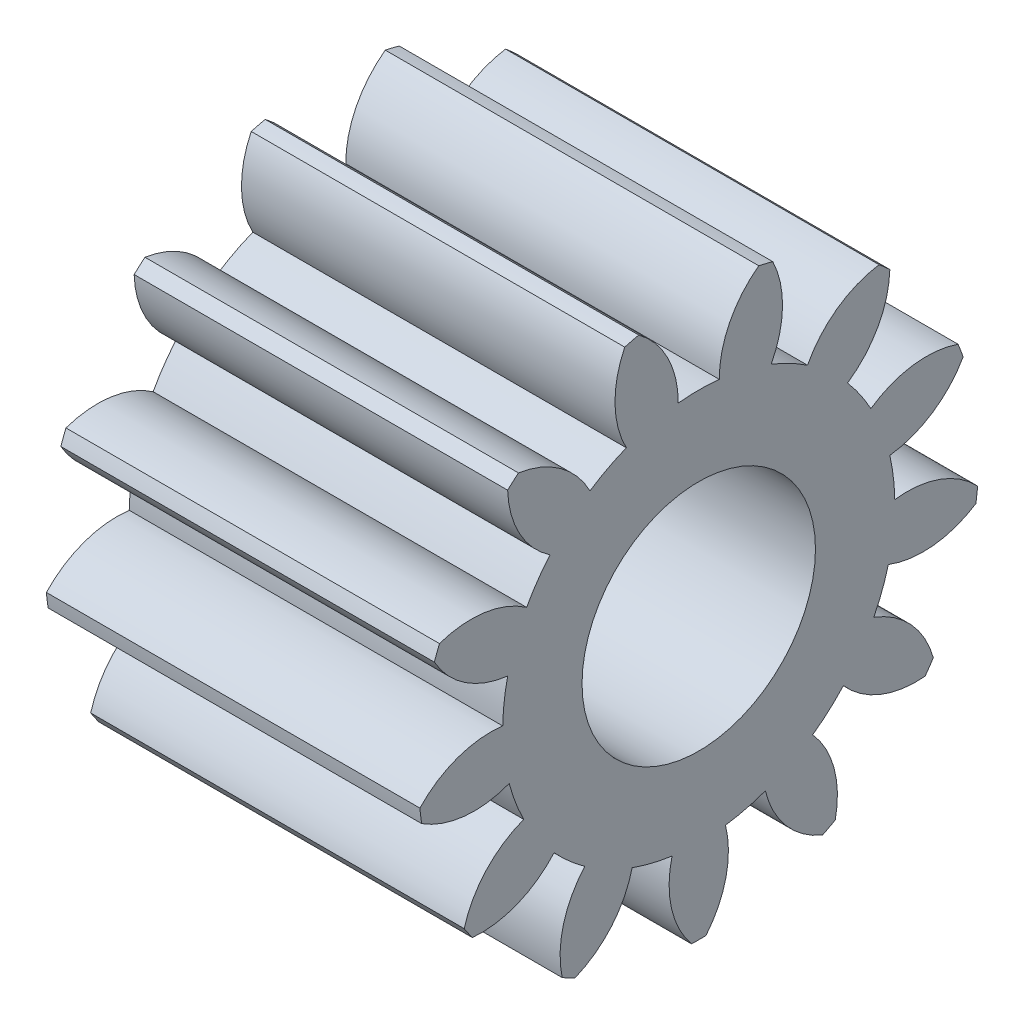
SolidWorks part; units mm, degrees
ref_plane "Plane1" through (0, 0, 0) normal (0, 0, 1) x (1, 0, 0)
ref_plane "Plane2" through (0, 0, 0) normal (0, 1, 0) x (1, 0, 0)
ref_plane "Plane3" through (0, 0, 0) normal (1, 0, 0) x (0, 0, -1)
other "Configuration Table"
sketch "HoldingSke" plane through (0, 0, 0) normal (0, 1, 0) x (1, 0, 0)
  line L0 (0, 0) -> (1.218, -0.2812)
  line L1 (-15, 0) -> (100, 0) construction
  line L2 (0, 0) -> (-2.1039, 2.3779)
  line L3 (0, 0) -> (-11.863, 4.5341)
  line L4 (0, 0) -> (8.4147, 1.9427)
  line L5 (0, 0) -> (-46.8476, -17.4728)
  line L6 (0, 0) -> (-6.6317, -4.4744)
  line L7 (-2.1039, 2.3779) -> (8.6586, 51.2059)
  line L8 (-76.2, 54.61) -> (-75.3, 54.61)
  line L9 (-71.009, 38.7566) -> (-53.1078, 45.2721)
  line L10 (-76.2, 71.12) -> (104.1128, 71.12)
  line L11 (0, 0) -> (-8, 0)
  line L12 (-76.2, 101.6) -> (-76.17, 101.6)
  line L13 (24.9733, 27.94) -> (52.9518, 28.4284)
  line L14 (24.9733, 27.94) -> (24.9743, 27.94)
  line L15 (24.9733, 27.94) -> (100.4006, 29.5858)
  line L16 (-63.627, -0.8) -> (-12.827, -0.8)
  circle A0 centre (0, 0) radius 2.5
  circle A1 centre (0, 0) radius 4.199
  circle A2 centre (0, 0) radius 37.5
  circle A3 centre (0, 0) radius 2.5
  dimension "MHD" = 8.398
  dimension "Hub_dia" = 75
  dimension "Bore" = 5
  dimension "MBD" = 5
  dimension "Num_teeth" = 13
  dimension "Pitch" = 1.25
  dimension "Overall_len" = 50
  dimension "Show_teeth" = 13
  dimension "Thickness" = 8
  dimension "OAL" = 50.0001
  dimension "T_dim" = 0.9
  dimension "Ap" = 20
  dimension "H" = 19.05
  dimension "Pitch_radius" = 180.3128
  dimension "Width" = 8
  dimension "Backlash" = 0.03
  dimension "Addendum_fac" = 1
  dimension "Dedendum_fac" = 1.25
  dimension "Clearance_fac" = 0.25
  dimension "Dedendum_add" = 0.001
  dimension "Module" = 0.8
sketch "BasProSke" plane through (0, 0, 0) normal (0, 1, 0) x (1, 0, 0)
  line L0 (-10, 0) -> (60, 0) construction
  line L1 (0, 0) -> (0, 6)
  line L2 (0, 0) -> (8, 0)
  line L3 (8, 0) -> (8, 6)
  line L4 (8, 6) -> (0, 6)
  dimension "Thickness" = 8
  dimension "Diameter" = 12
revolve "Base-Revolve" add sketch "BasProSke" angle 360 about L0
sketch "TooCutSke" plane through (0, 0, 0) normal (1, 0, 0) x (0, 0, -1)
  line L1 (0, 0) -> (0, 107) construction
  line L2 (0, 0) -> (-0.6792, 5.1554) construction
  line L3 (0, 0) -> (-2.4737, 10.036) construction
  line L4 (-0.6792, 5.1554) -> (-1.2368, 5.018) construction
  arc A0 (0.4398, 4.1759) -> (-0.4398, 4.1759) centre (0, 0) ccw
  arc A1 (1.3129, 5.8806) -> (-1.3129, 5.8806) centre (0, 0) ccw
  circle A2 centre (0, 0) radius 5.2 construction
  circle A3 centre (0, 0) radius 4.8864 construction
  arc A4 (-0.4398, 4.1759) -> (-1.3129, 5.8806) centre (-2.5198, 4.1866) ccw
  arc A5 (1.3129, 5.8806) -> (0.4398, 4.1759) centre (2.5198, 4.1866) ccw
  dimension "Root_dia" = 8.398
  dimension "Overcut_dia" = 12.0508
  dimension "Pitch_dia" = 10.4
  dimension "Base_dia" = 9.7728
  dimension "Flank_rad" = 2.08
  dimension "Half_ang" = 13.846
  dimension "Half_CT" = 0.5743
extrude "ToothCut" cut sketch "TooCutSke" along normal through all
fillet "Breaks" [suppressed] radius 0.016
fillet "RootFillets" [suppressed] radius 0.201
pattern_circular "TeethCuts" count 13 every 27.692 about axis through (-10, 0, 0) along (1, 0, 0) of "ToothCut", "RootFillets", "Breaks"
sketch "HubNeaOneSke" plane through (0, 0, 0) normal (-1, 0, 0) x (0, 0, 1)
  circle A0 centre (0, 0) radius 4.199
  dimension "Diameter" = 8.398
extrude "HubNearOne" [suppressed] add sketch "HubNeaOneSke" along normal blind 42.0001
sketch "HubNeaBotSke" plane through (0, 0, 0) normal (-1, 0, 0) x (0, 0, 1)
  circle A0 centre (0, 0) radius 4.199
  dimension "Diameter" = 8.398
extrude "HubNearBoth" [suppressed] add sketch "HubNeaBotSke" along normal blind 21
ref_plane "FarPln" through (8, 0, 0) normal (1, 0, 0) x (0, 0, -1)
sketch "HubFarSke" plane through (8, 0, 0) normal (1, 0, 0) x (0, 0, -1)
  circle A0 centre (0, 0) radius 4.199
  dimension "Diameter" = 8.398
extrude "HubFar" [suppressed] add sketch "HubFarSke" along normal blind 21
sketch "BorSke" plane through (0, 0, 0) normal (1, 0, 0) x (0, 0, -1)
  circle A0 centre (0, 0) radius 2.5
  dimension "Diameter" = 5
extrude "Bore" cut sketch "BorSke" along normal mid plane 100.0001
sketch "KeySke" plane through (0, 0, 0) normal (1, 0, 0) x (0, 0, -1)
  line L0 (-1, 0) -> (-1, 3.4)
  line L1 (-1, 3.4) -> (1, 3.4)
  line L2 (1, 3.4) -> (1, 0)
  line L3 (0, 0) -> (0, 34) construction
  line L4 (-1, 0) -> (1, 0)
  dimension "Offset" = 3.4
  dimension "Width" = 2
extrude "Keyway" [suppressed] cut sketch "KeySke" along normal mid plane 100.0001
pattern_circular "Keyway2" [suppressed] count 2 every 90 about axis through (-10, 0, 0) along (1, 0, 0)
equation "' \"Module@HoldingSke\" = 6.35"
equation "' \"Num_teeth@HoldingSke\" = 12"
equation "' \"Ap@HoldingSke\" =  20"
equation "' \"Ap@HoldingSke\" = 20"
equation "' \"Width@HoldingSke\" = 0.5 * 25.4"
equation "' \"Hub_dia@HoldingSke\"= 1 * 25.4"
equation "' \"Hub_dia@HoldingSke\" = 1 * 25.4"
equation "' \"Overall_len@HoldingSke\" = 1.0 * 25.4"
equation "' \"Bore@HoldingSke\" = 0.75 * 25.4"
equation "' \"T_dim@HoldingSke\" = 0.1 * 25.4"
equation "' \"Width@KeySke\" = 0.25 * 25.4"
equation "' \"Show_teeth@HoldingSke\" = 13"
equation "' \"Backlash@HoldingSke\" = 0.009 * 25.4"
equation "' \"Addendum_fac@HoldingSke\" = 1.0"
equation "' \"Dedendum_fac@HoldingSke\" = 1.25"
equation "' \"Dedendum_add@HoldingSke\" = 0.00005 * 25.4"
equation "' \"Clearance_fac@HoldingSke\" = 0.25"
equation "\"Pitch@HoldingSke\" = 1 / \"Module@HoldingSke\""
equation "\"Overcut_dia@TooCutSke\" = (\"Num_teeth@HoldingSke\" + 2 * \"Addendum_fac@HoldingSke\") / \"Pitch@HoldingSke\" + 0.002 * 25.4"
equation "\"Pitch_dia@TooCutSke\" = \"Num_teeth@HoldingSke\" / \"Pitch@HoldingSke\""
equation "\"Base_dia@TooCutSke\" = \"Num_teeth@HoldingSke\" / \"Pitch@HoldingSke\" * cos((\"Ap@HoldingSke\"  * 3.14159265 / 180))"
equation "\"Root_dia@TooCutSke\" = (\"Num_teeth@HoldingSke\" + 2) / \"Pitch@HoldingSke\" - 2 * (\"Addendum_fac@HoldingSke\" + \"Dedendum_fac@HoldingSke\") / \"Pitch@HoldingSke\" - \"Dedendum_add@HoldingSke\" * 2"
equation "\"Half_ang@TooCutSke\" = 180 / \"Num_teeth@HoldingSke\""
equation "\"Half_CT@TooCutSke\" = \"Num_teeth@HoldingSke\" / \"Pitch@HoldingSke\" * sin((3.14159265 / 2 / \"Num_teeth@HoldingSke\")) / 2 - 7 * \"Backlash@HoldingSke\" / 4"
equation "\"Flank_rad@TooCutSke\" = \"Num_teeth@HoldingSke\" / \"Pitch@HoldingSke\" / 5"
equation "\"Radius@RootFillets\" = \"Clearance_fac@HoldingSke\" / \"Pitch@HoldingSke\" + \"Dedendum_add@HoldingSke\""
equation "\"Break_rad@Breaks\" = 0.02 / \"Pitch@HoldingSke\""
equation "\"Thickness@HoldingSke\" = \"Width@HoldingSke\""
equation "\"OAL@HoldingSke\" = \"Thickness@HoldingSke\""
equation "\"MHD@HoldingSke\" = (\"Num_teeth@HoldingSke\" + 2) / \"Pitch@HoldingSke\" - 2 * (\"Addendum_fac@HoldingSke\" + \"Dedendum_fac@HoldingSke\")  / \"Pitch@HoldingSke\" - \"Dedendum_add@HoldingSke\" * 2"
equation "\"MBD@HoldingSke\" = (\"Num_teeth@HoldingSke\" + 2) / \"Pitch@HoldingSke\" - 2 * (\"Addendum_fac@HoldingSke\" + \"Dedendum_fac@HoldingSke\")  / \"Pitch@HoldingSke\" - \"Dedendum_add@HoldingSke\" * 2 - 0.002 * 25.4"
equation "\"MHD@HoldingSke\" = ((sgn( \"MHD@HoldingSke\" - \"Hub_dia@HoldingSke\" )-1)*( \"MHD@HoldingSke\" - \"Hub_dia@HoldingSke\" ))/-2+ \"Hub_dia@HoldingSke\""
equation "\"MBD@HoldingSke\" = ((sgn( \"MBD@HoldingSke\" - \"Bore@HoldingSke\" )-1)*( \"MBD@HoldingSke\" - \"Bore@HoldingSke\" ))/-2+ \"Bore@HoldingSke\""
equation "\"OAL@HoldingSke\" = ((sgn( \"OAL@HoldingSke\" - \"Overall_len@HoldingSke\" )+1)*( \"OAL@HoldingSke\" - \"Overall_len@HoldingSke\" ))/2 + \"Overall_len@HoldingSke\" + 0.000002 * 25.4"
equation "\"Num_teeth@TeethCuts\" = int( \"Show_teeth@HoldingSke\" ) + 1"
equation "\"Num_teeth@TeethCuts\" = ((sgn( \"Num_teeth@TeethCuts\" - \"Num_teeth@HoldingSke\" )-1)*( \"Num_teeth@TeethCuts\" - \"Num_teeth@HoldingSke\" ))/-2+ \"Num_teeth@HoldingSke\""
equation "\"Num_teeth@TeethCuts\" = ((sgn( \"Num_teeth@TeethCuts\" - 2.0)+1)*( \"Num_teeth@TeethCuts\" - 2.0))/2 +2.0"
equation "\"Angle@TeethCuts\" = 360.0 / \"Num_teeth@HoldingSke\""
equation "\"Diameter@BasProSke\" = (\"Num_teeth@HoldingSke\" + 2 * \"Addendum_fac@HoldingSke\") / \"Pitch@HoldingSke\""
equation "\"Thickness@BasProSke\"  = \"Thickness@HoldingSke\""
equation "' \"Fillet_rad@BasProSke\" =  \"Thickness@HoldingSke\" * 0.05"
equation "' \"Fillet_rad@BasProSke\" = \"Thickness@HoldingSke\" * 0.05"
equation "\"MHD@HoldingSke\" = ((sgn( \"MHD@HoldingSke\" - \"Root_dia@TooCutSke\" )-1)*( \"MHD@HoldingSke\" - \"Root_dia@TooCutSke\" ))/-2+ \"Root_dia@TooCutSke\""
equation "\"Diameter@HubNeaOneSke\" = \"MHD@HoldingSke\""
equation "\"Length@HubNearOne\" = \"OAL@HoldingSke\" - \"Thickness@BasProSke\""
equation "\"Diameter@HubNeaBotSke\" = \"MHD@HoldingSke\""
equation "\"Length@HubNearBoth\" = ( \"OAL@HoldingSke\" - \"Thickness@BasProSke\" ) / 2.0"
equation "\"Thickness@FarPln\" = \"Thickness@BasProSke\""
equation "\"Diameter@HubFarSke\" = \"MHD@HoldingSke\""
equation "\"Length@HubFar\" = ( \"OAL@HoldingSke\" - \"Thickness@BasProSke\" ) / 2.0"
equation "\"Diameter@BorSke\" = \"MBD@HoldingSke\""
equation "\"D1@Bore\" = \"OAL@HoldingSke\" * 2.0"
equation "\"D1@Keyway\" = \"OAL@HoldingSke\" * 2.0"
equation "\"Offset@KeySke\" = \"T_dim@HoldingSke\" + \"MBD@HoldingSke\" / 2.0"
